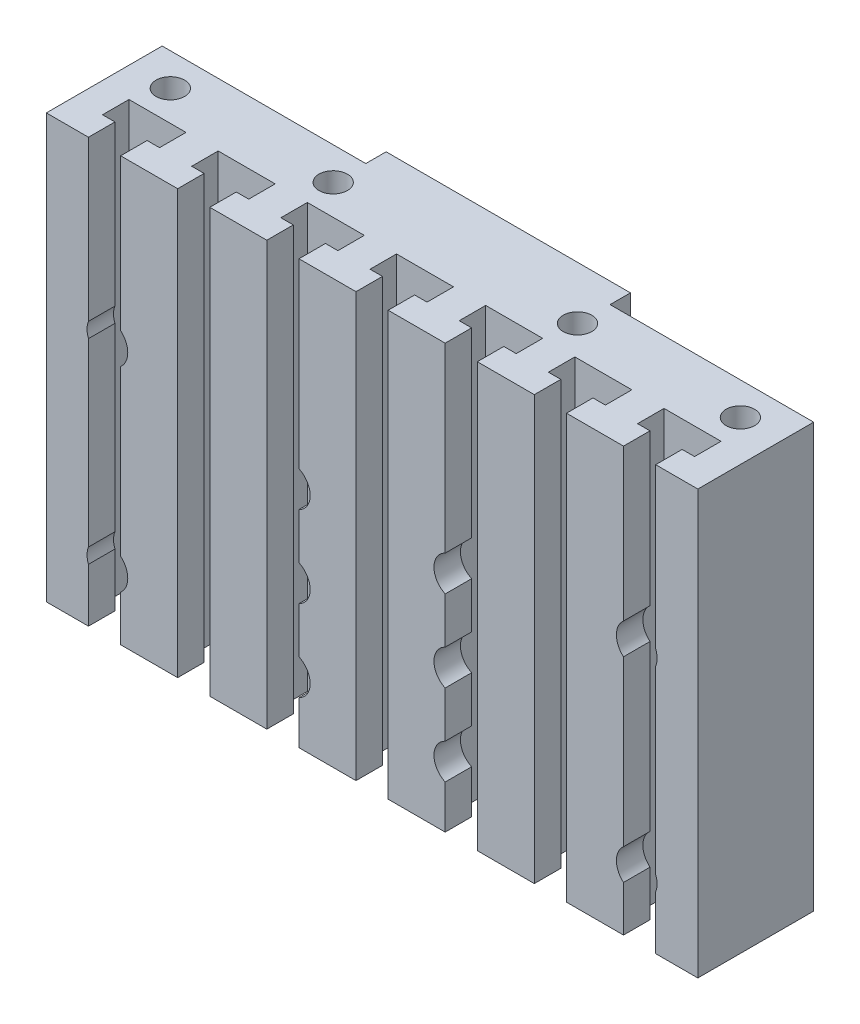
SolidWorks part; units mm, degrees
ref_plane "Front Plane" through (0, 0, 0) normal (0, 0, 1) x (1, 0, 0)
ref_plane "Top Plane" through (0, 0, 0) normal (0, 1, 0) x (1, 0, 0)
ref_plane "Right Plane" through (0, 0, 0) normal (1, 0, 0) x (0, 0, -1)
sketch "Sketch1" plane through (0, 0, 0) normal (0, 0, 1) x (1, 0, 0)
  line L0 (0, 52) -> (0, -52) construction
  line L1 (-80, 52) -> (80, 52)
  line L2 (-80, 52) -> (-80, -52)
  line L3 (-80, -52) -> (80, -52)
  line L4 (80, 52) -> (80, -52)
  line L5 (-80, 52) -> (80, -52) construction
  line L6 (-80, -52) -> (80, 52) construction
  line L7 (20, 52) -> (20, -55.7258) construction
  circle A0 centre (20, -37) radius 2.5
  circle A1 centre (-20, -37) radius 2.5
  circle A2 centre (20, -17) radius 2.5
  circle A3 centre (20, 3) radius 2.5
  circle A4 centre (-20, 3) radius 2.5
  circle A5 centre (-20, -17) radius 2.5
  point P0 (0, 0)
  dimension "D4" = 5
  dimension "D1" = 160
  dimension "D2" = 104
  dimension "D3" = 40
  dimension "D5" = 15
  dimension "D6" = 20
  dimension "D7" = 20
extrude "Boss-Extrude1" add sketch "Sketch1" along normal blind 28.45
sketch "Sketch2" plane through (0, 52, 0) normal (0, 1, 0) x (1, 0, 0)
  line L0 (80, -28.45) -> (-80, -28.45) construction
  line L1 (-3.95, -28.45) -> (3.95, -28.45)
  line L2 (-3.95, -28.45) -> (-3.95, -21.95)
  line L4 (3.95, -28.45) -> (3.95, -21.95)
  line L5 (3.95, -21.95) -> (7, -21.95)
  line L6 (-7, -15.45) -> (7, -15.45)
  line L7 (-7, -15.45) -> (-7, -21.95)
  line L8 (-7, -21.95) -> (-3.95, -21.95)
  line L9 (7, -15.45) -> (7, -21.95)
  line L10 (0, 0) -> (0, -28.45) construction
  line L11 (80, 0) -> (-80, 0) construction
  line L12 (25.85, -28.45) -> (25.85, -21.95)
  line L13 (17.95, -28.45) -> (25.85, -28.45)
  line L14 (25.85, -21.95) -> (28.9, -21.95)
  line L15 (28.9, -15.45) -> (28.9, -21.95)
  line L16 (14.9, -15.45) -> (28.9, -15.45)
  line L17 (14.9, -15.45) -> (14.9, -21.95)
  line L18 (14.9, -21.95) -> (17.95, -21.95)
  line L19 (17.95, -28.45) -> (17.95, -21.95)
  line L20 (47.75, -28.45) -> (47.75, -21.95)
  line L21 (39.85, -28.45) -> (47.75, -28.45)
  line L22 (47.75, -21.95) -> (50.8, -21.95)
  line L23 (50.8, -15.45) -> (50.8, -21.95)
  line L24 (36.8, -15.45) -> (50.8, -15.45)
  line L25 (36.8, -15.45) -> (36.8, -21.95)
  line L26 (36.8, -21.95) -> (39.85, -21.95)
  line L27 (39.85, -28.45) -> (39.85, -21.95)
  line L28 (69.65, -28.45) -> (69.65, -21.95)
  line L29 (61.75, -28.45) -> (69.65, -28.45)
  line L30 (69.65, -21.95) -> (72.7, -21.95)
  line L31 (72.7, -15.45) -> (72.7, -21.95)
  line L32 (58.7, -15.45) -> (72.7, -15.45)
  line L33 (58.7, -15.45) -> (58.7, -21.95)
  line L34 (58.7, -21.95) -> (61.75, -21.95)
  line L35 (61.75, -28.45) -> (61.75, -21.95)
  line L36 (-28.9, -15.45) -> (-28.9, -21.95)
  line L37 (-28.9, -21.95) -> (-25.85, -21.95)
  line L38 (-25.85, -28.45) -> (-25.85, -21.95)
  line L39 (-28.9, -15.45) -> (-14.9, -15.45)
  line L40 (-14.9, -15.45) -> (-14.9, -21.95)
  line L41 (-17.95, -28.45) -> (-17.95, -21.95)
  line L42 (-25.85, -28.45) -> (-17.95, -28.45)
  line L43 (-17.95, -21.95) -> (-14.9, -21.95)
  line L44 (-50.8, -15.45) -> (-50.8, -21.95)
  line L45 (-50.8, -21.95) -> (-47.75, -21.95)
  line L46 (-47.75, -28.45) -> (-47.75, -21.95)
  line L47 (-50.8, -15.45) -> (-36.8, -15.45)
  line L48 (-36.8, -15.45) -> (-36.8, -21.95)
  line L49 (-39.85, -28.45) -> (-39.85, -21.95)
  line L50 (-47.75, -28.45) -> (-39.85, -28.45)
  line L51 (-39.85, -21.95) -> (-36.8, -21.95)
  line L52 (-72.7, -15.45) -> (-72.7, -21.95)
  line L53 (-72.7, -21.95) -> (-69.65, -21.95)
  line L54 (-69.65, -28.45) -> (-69.65, -21.95)
  line L55 (-72.7, -15.45) -> (-58.7, -15.45)
  line L56 (-58.7, -15.45) -> (-58.7, -21.95)
  line L57 (-61.75, -28.45) -> (-61.75, -21.95)
  line L58 (-69.65, -28.45) -> (-61.75, -28.45)
  line L59 (-61.75, -21.95) -> (-58.7, -21.95)
  point P14 (0, -15.45)
  dimension "D1" = 14
  dimension "D2" = 7.9
  dimension "D3" = 6.5
  dimension "D4" = 6.5
  dimension "D6" = 7.9
  dimension "D8" = 7.9
  dimension "D5" = 4
  dimension "D7" = 4
extrude "Cut-Extrude1" cut sketch "Sketch2" against normal through all
sketch "Sketch5" plane through (0, 0, 0) normal (0, 0, -1) x (-1, 0, 0)
  line L0 (0, 52) -> (0, -52) construction
  line L1 (-80, 52) -> (80, 52) construction
  line L2 (80, -52) -> (-80, -52) construction
  line L4 (-30, -52) -> (30, -52)
  line L5 (-30, -52) -> (-30, 52)
  line L6 (-30, 52) -> (30, 52)
  line L7 (30, -52) -> (30, 52)
  point P10 (0, 52)
  dimension "D1" = 60
extrude "Boss-Extrude2" add sketch "Sketch5" along normal blind 5
sketch "Sketch3" plane through (0, 0, 28.45) normal (0, 0, 1) x (1, 0, 0)
  circle A0 centre (-20, 3) radius 4.8
  circle A1 centre (20, 3) radius 4.8
  circle A2 centre (-20, -17) radius 4.8
  circle A3 centre (20, -17) radius 4.8
  circle A4 centre (-20, -37) radius 4.8
  circle A5 centre (20, -37) radius 4.8
  dimension "D1" = 9.6
extrude "Cut-Extrude2" cut sketch "Sketch3" against normal blind 7
sketch "Sketch4" plane through (0, 0, 15.45) normal (0, 0, 1) x (1, 0, 0)
  circle A0 centre (-20, 3) radius 4.8
  circle A1 centre (20, 3) radius 4.8
  circle A2 centre (-20, -17) radius 4.8
  circle A3 centre (20, -17) radius 4.8
  circle A4 centre (-20, -37) radius 4.8
  circle A5 centre (20, -37) radius 4.8
  dimension "D1" = 9.6
extrude "Cut-Extrude3" cut sketch "Sketch4" against normal blind 13.35 from surface at 6.5 starting at face at (-16.515, -10.2, 21.95)
sketch "Sketch6" plane through (0, 0, 0) normal (0, 0, 1) x (1, 0, 0)
  circle A0 centre (-20, 3) radius 2.5
  circle A1 centre (20, 3) radius 2.5
  circle A2 centre (-20, -17) radius 2.5
  circle A3 centre (20, -17) radius 2.5
  circle A4 centre (20, -37) radius 2.5
  circle A5 centre (-20, -37) radius 2.5
  dimension "D1" = 5
extrude "Cut-Extrude4" cut sketch "Sketch6" against normal through all
sketch "Sketch7" plane through (0, 52, 0) normal (0, 1, 0) x (1, 0, 0)
  line L0 (-80, -8) -> (80, -8) construction
  line L1 (-80, -28.45) -> (-80, 0) construction
  line L2 (80, -28.45) -> (80, 0) construction
  line L4 (-30, 0) -> (-80, 0) construction
  line L6 (0, 5) -> (0, -15.45) construction
  line L7 (-30, 5) -> (30, 5) construction
  line L8 (7, -15.45) -> (-7, -15.45) construction
  circle A0 centre (-70, -8) radius 3.5
  circle A1 centre (-30, -8) radius 3.5
  circle A2 centre (70, -8) radius 3.5
  circle A3 centre (30, -8) radius 3.5
  dimension "D1" = 7
  dimension "D3" = 40
  dimension "D2" = 10
  dimension "D4" = 8
extrude "Cut-Extrude5" cut sketch "Sketch7" against normal blind 12
sketch "Sketch8" plane through (0, -52, 0) normal (0, -1, 0) x (1, 0, 0)
  line L0 (80, 8) -> (-80, 8) construction
  line L1 (80, 28.45) -> (80, 0) construction
  line L2 (-80, 28.45) -> (-80, 0) construction
  line L3 (30, 0) -> (80, 0) construction
  line L6 (0, -5) -> (0, 15.45) construction
  line L7 (30, -5) -> (-30, -5) construction
  line L8 (7, 15.45) -> (-7, 15.45) construction
  circle A0 centre (70, 8) radius 3.5
  circle A1 centre (30, 8) radius 3.5
  circle A2 centre (-30, 8) radius 3.5
  circle A3 centre (-70, 8) radius 3.5
  dimension "D1" = 7
  dimension "D2" = 10
  dimension "D3" = 40
  dimension "D4" = 8
extrude "Cut-Extrude6" cut sketch "Sketch8" against normal blind 12
sketch "Sketch9" plane through (0, 0, 28.45) normal (0, 0, 1) x (1, 0, 0)
  line L0 (0, 47.1529) -> (0, -45.7832) construction
  line L1 (-80, -52) -> (-69.65, -52) construction
  line L2 (-65, 11) -> (65, 11) construction
  line L3 (-65, 11) -> (-65, -37) construction
  line L4 (-65, -37) -> (65, -37) construction
  line L5 (65, 11) -> (65, -37) construction
  circle A0 centre (-65, 11) radius 5
  circle A1 centre (-65, -37) radius 5
  circle A2 centre (65, -37) radius 5
  circle A3 centre (65, 11) radius 5
  point P3 (0, 11)
  point P8 (-65, -13)
  dimension "D3" = 10
  dimension "D1" = 130
  dimension "D2" = 48
  dimension "D4" = 15
extrude "Cut-Extrude7" cut sketch "Sketch9" against normal blind 26
